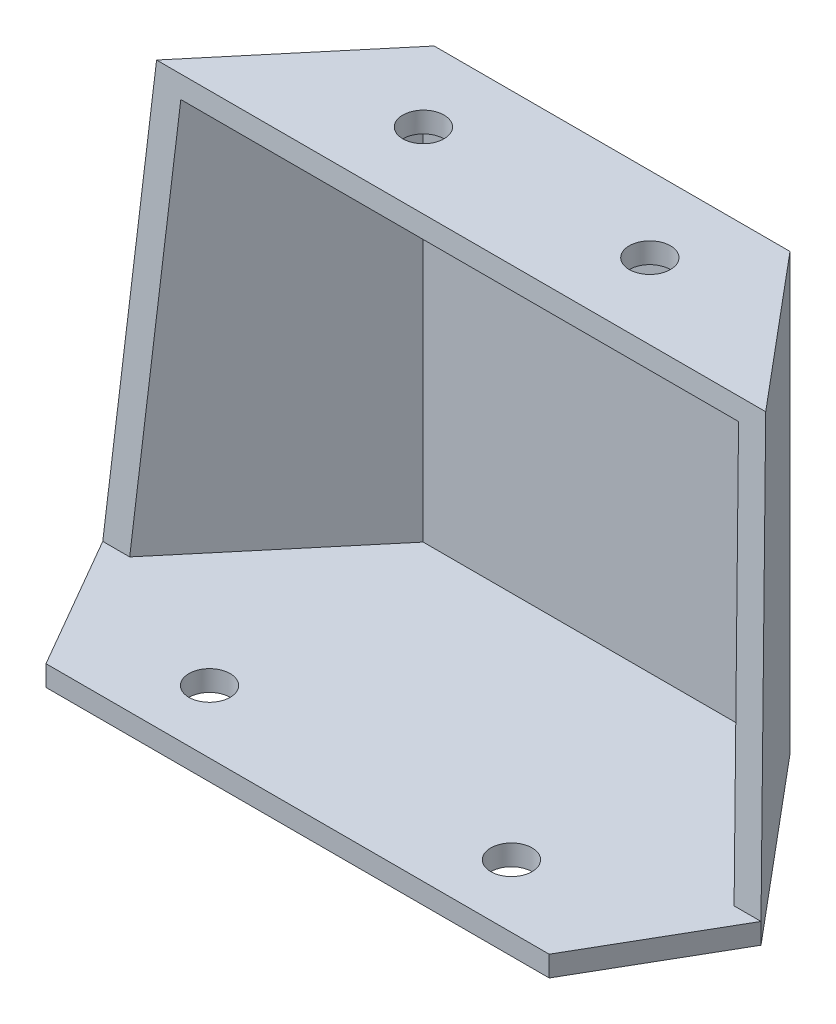
SolidWorks part; units mm, degrees
ref_plane "前视基准面" through (0, 0, 0) normal (0, 0, 1) x (1, 0, 0)
ref_plane "上视基准面" through (0, 0, 0) normal (0, 1, 0) x (1, 0, 0)
ref_plane "右视基准面" through (0, 0, 0) normal (1, 0, 0) x (0, 0, -1)
other "Configuration Table"
sketch "草图1" plane through (0, 0, 0) normal (0, 1, 0) x (1, 0, 0)
  line L0 (0, -29.5161) -> (0, -182.0161) construction
  line L8 (-122, -182.0161) -> (122, -182.0161)
  line L9 (122, -182.0161) -> (159.5924, -116.9043)
  line L10 (159.5924, -116.9043) -> (86.265, -29.5161)
  line L11 (86.265, -29.5161) -> (-86.265, -29.5161)
  line L12 (-159.5924, -116.9043) -> (-86.265, -29.5161)
  line L13 (-122, -182.0161) -> (-159.5924, -116.9043)
  dimension "D1" = 244
  dimension "D2" = 172.53
  dimension "D3" = 152.5
  dimension "D4" = 80
  dimension "D5" = 60
extrude "凸台-拉伸1" add sketch "草图1" along normal blind 211
shell "抽壳7" thickness 10
sketch "草图4" plane through (0, 0, 0) normal (1, 0, 0) x (0, 0, -1)
  line L1 (-29.5161, 211) -> (-29.5161, 0) construction
  line L2 (-116.9043, 211) -> (-116.9043, 0) construction
  line L4 (-102.7161, 211) -> (-182.0161, 211)
  line L5 (-116.9043, 10) -> (-102.7161, 211)
  line L6 (-116.9043, 211) -> (-29.5161, 211) construction
  line L7 (-182.0161, 211) -> (-182.0161, 10)
  line L8 (-182.0161, 211) -> (-182.0161, 0) construction
  line L9 (-182.0161, 10) -> (-116.9043, 10)
  dimension "D2" = 73.2
extrude "切除-拉伸3" cut sketch "草图4" against normal through all both and the other way through all
sketch "草图7" plane through (0, 211, 0) normal (0, 1, 0) x (1, 0, 0)
  line L0 (0, 0) -> (0, -82.0756) construction
  line L1 (86.265, -29.5161) -> (-86.265, -29.5161) construction
  circle A0 centre (-54.9, -66.1161) radius 10
  circle A1 centre (54.9, -66.1161) radius 10
  dimension "D3" = 20
  dimension "D1" = 109.8
  dimension "D2" = 36.6
extrude "切除-拉伸4" cut sketch "草图7" against normal up to next
sketch "草图8" plane through (0, 10, 0) normal (0, 1, 0) x (1, 0, 0)
  line L0 (0, 0) -> (0, -170.4672) construction
  line L2 (-122, -182.0161) -> (122, -182.0161) construction
  circle A0 centre (-73.2, -151.5161) radius 10
  circle A1 centre (73.2, -151.5161) radius 10
  point P7 (-82.4192, -182.0161)
  point P8 (-86.0026, -176.8377)
  dimension "D3" = 20
  dimension "D1" = 146.4
  dimension "D2" = 30.5
extrude "切除-拉伸5" cut sketch "草图8" against normal up to next
